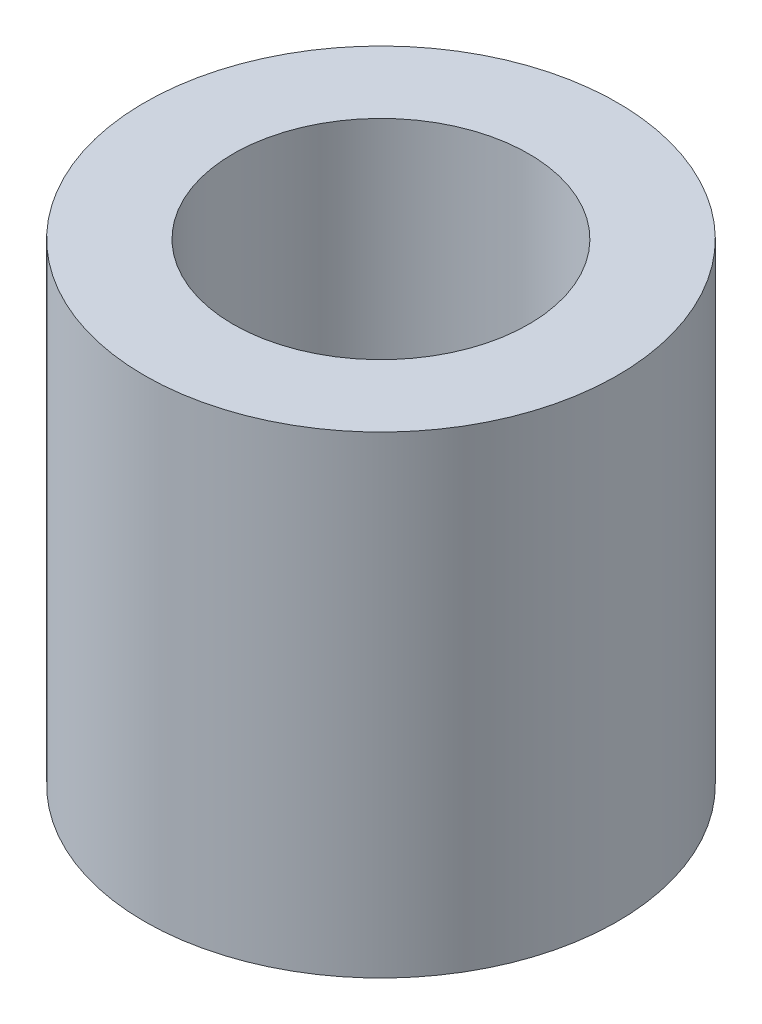
SolidWorks part; units mm, degrees
ref_plane "前视基准面" through (0, 0, 0) normal (0, 0, 1) x (1, 0, 0)
ref_plane "上视基准面" through (0, 0, 0) normal (0, 1, 0) x (1, 0, 0)
ref_plane "右视基准面" through (0, 0, 0) normal (1, 0, 0) x (0, 0, -1)
other "Configuration Table"
sketch "草图1" plane through (0, 0, 0) normal (0, 1, 0) x (1, 0, 0)
  circle A0 centre (0, 0) radius 2.5
  circle A1 centre (0, 0) radius 4
  dimension "D1" = 5
  dimension "D2" = 8
extrude "凸台-拉伸1" add sketch "草图1" along normal blind 8
